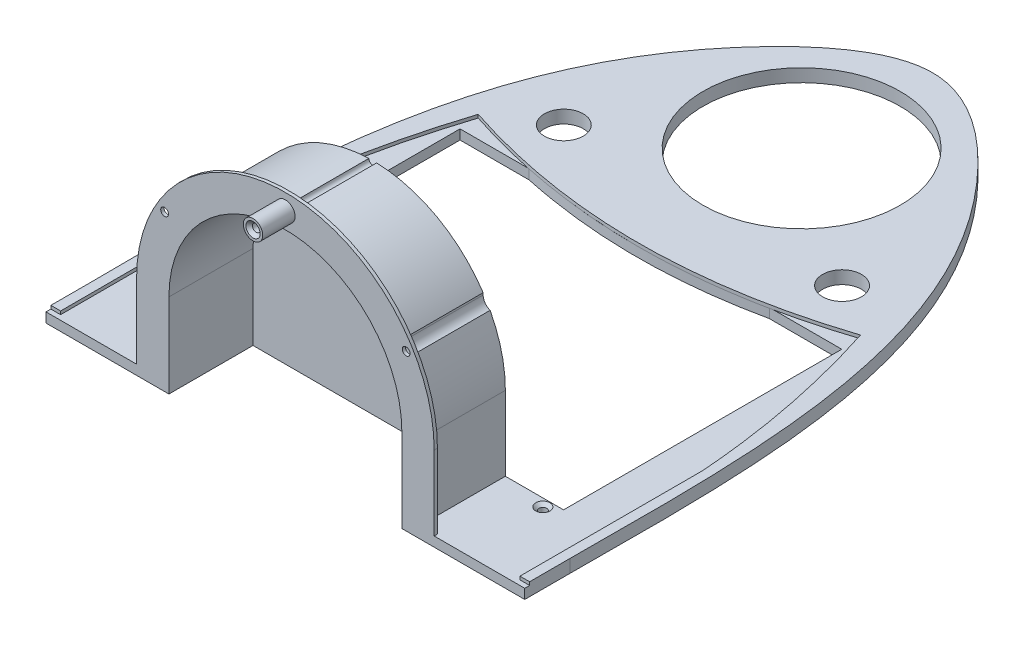
SolidWorks part; units mm, degrees
material "PET"
ref_plane "Front" through (0, 0, 0) normal (0, 0, 1) x (1, 0, 0)
ref_plane "Top" through (0, 0, 0) normal (0, 1, 0) x (1, 0, 0)
ref_plane "Right" through (0, 0, 0) normal (1, 0, 0) x (0, 0, -1)
sketch "Sketch3" plane through (0, 0, 0) normal (0, 1, 0) x (1, 0, 0)
  line L6 (-74, 0) -> (-74, -14)
  line L7 (-74, -14) -> (74, -14)
  line L8 (74, -14) -> (74, 0)
  circle A0 centre (0, 145.589) radius 30.5008
  circle A1 centre (-43.002, 115.0882) radius 5.9957
  circle A2 centre (43.0023, 115.0882) radius 6.0049
  spline S0 degree 3 poles (74, 0) (74.2312, 56.044) (77.0237, 134.8914) (0.0005, 195.647) (-77.0188, 134.8892) (-74.2322, 56.0447) (-74, 0) knots 0 0 0 0 0.40663 0.500002 0.593368 1 1 1 1
extrude "Boss-Extrude1" add sketch "Sketch3" along normal blind 4
sketch "Sketch4" plane through (0, 4, 0) normal (0, 1, 0) x (1, 0, 0)
  line L6 (71.0001, 44.0011) -> (71.0001, 6.0671)
  line L8 (71.0001, 5.9382) -> (71.0001, -16.9987)
  line L9 (-70.9967, 6.0027) -> (-70.9967, 44.0011)
  line L11 (71.0001, -16.9987) -> (-70.9967, -16.9987)
  line L12 (-70.9967, -16.9987) -> (-70.9967, 6.0027)
  line L14 (-38.3482, 99.0875) -> (-43.002, 99.0875)
  line L15 (71.0001, 6.0671) -> (71.0001, 5.9382)
  spline S2 degree 3 poles (-59.0924, 104.7018) (-39.395, 98.236) (0.0027, 91.7694) (39.4006, 98.2356) (59.1009, 104.7026) knots 0.007529 0.007529 0.007529 0.007529 0.499976 0.992492 0.992492 0.992492 0.992492
  spline S3 degree 3 poles (59.1009, 104.7026) (65.5244, 84.7081) (69.4908, 64.4742) (71.0001, 44.0011) knots 0.003068 0.003068 0.003068 0.003068 0.620646 0.620646 0.620646 0.620646
  spline S4 degree 3 poles (-59.0924, 104.7018) (-65.5187, 84.7077) (-69.4868, 64.4742) (-70.9967, 44.0011) knots 0.003077 0.003077 0.003077 0.003077 0.62065 0.62065 0.62065 0.62065
extrude "Cut-Extrude1" cut sketch "Sketch4" against normal blind 1 and the other way through all
sketch "Sketch5" plane through (0, 3, 0) normal (0, 1, 0) x (1, 0, 0)
  line L0 (-37.6312, 99) -> (-59.0046, 99)
  line L1 (36.6037, 99) -> (59.004, 99)
  line L2 (-59.0046, 99) -> (-59.0046, 13)
  line L5 (59.004, 99) -> (59.004, 13)
  line L6 (59.004, 13) -> (-59.0046, 13)
  spline S0 degree 2 poles (-37.6312, 99) (-0.5019, 91.0036) (36.6037, 99) knots 0 0 0 1 1 1
  spline S1 degree 3 poles (59.1009, 104.7026) (19.703, 91.7695) (-19.6948, 91.7692) (-59.0924, 104.7018) knots 0.007529 0.007529 0.007529 0.007529 0.992492 0.992492 0.992492 0.992492 construction
  dimension "D1" = 86
extrude "Cut-Extrude2" cut sketch "Sketch5" against normal blind 10
sketch "Sketch7" plane through (0, 3, 0) normal (0, 1, 0) x (1, 0, 0)
  line L0 (-0.0003, 13) -> (-45.9987, 13)
  line L1 (-59.0046, 13) -> (59.004, 13) construction
  line L2 (-45.9987, 13) -> (-45.9987, -14)
  line L3 (-70.9967, -14) -> (71.0001, -14) construction
  line L4 (-45.9987, -14) -> (0.0017, -14)
  line L5 (0.0017, -14) -> (46.0044, -14)
  line L6 (46.0044, -14) -> (46.0044, 13)
  line L7 (46.0044, 13) -> (-0.0003, 13)
extrude "Boss-Extrude2" add sketch "Sketch7" along normal blind 23
sketch "Sketch8" plane through (0, 26, 0) normal (0, 1, 0) x (1, 0, 0)
  line L0 (0.0029, 13) -> (0.0029, -14)
  line L1 (46.0044, 13) -> (-45.9987, 13) construction
  line L2 (-45.9987, -14) -> (46.0044, -14) construction
  line L3 (0.0029, -14) -> (-45.9987, -14)
  line L4 (-45.9987, -14) -> (-45.9987, 13)
  line L5 (-45.9987, 13) -> (0.0029, 13)
revolve "Revolve1" add sketch "Sketch8" angle 180 about L0
sketch "Sketch9" plane through (0, 0, -13) normal (0, 0, -1) x (-1, 0, 0)
  line L0 (-0.0029, 67.0051) -> (-0.0029, 66.9999)
  line L2 (74.091, 4) -> (-74.0909, 4) construction
  line L3 (-46.0044, 26) -> (-46.0044, 3) construction
  line L5 (45.9987, 26) -> (45.9987, 3) construction
  line L6 (-46.0044, 4) -> (-46.0044, 26)
  line L7 (-41.0083, 4) -> (-41.0083, 26)
  line L8 (41.002, 4) -> (41.002, 26)
  line L9 (45.9987, 3) -> (45.9987, 4)
  line L10 (45.9987, 4) -> (45.9987, 26)
  line L11 (41.002, 4) -> (41.002, 3)
  line L12 (41.002, 3) -> (45.9987, 3)
  line L13 (-46.0044, 3) -> (-46.0044, 4)
  line L14 (-46.0044, 3) -> (-41.0083, 3)
  line L15 (-41.0083, 3) -> (-41.0083, 4)
  arc A1 (-41.0083, 26) -> (41.002, 26) centre (-0.0031, 26) cw
  arc A2 (-46.0044, 26) -> (45.9987, 26) centre (-0.0029, 26) cw
extrude "Cut-Extrude3" cut sketch "Sketch9" against normal blind 26
fillet "Fillet1" radius 1 3 edges at (-41.002, 14.5, 13) (41.0083, 14.5, 13) (0.0031, 67.0051, 13)
sketch "Sketch10" plane through (0, 0, -13) normal (0, 0, -1) x (-1, 0, 0)
  point P8 (-37.3413, 48.1051)
  point P10 (37.3365, 48.1051)
hole_wizard "CSK for M2 Countersunk Raised Head Screw1" positions "3DSketch1" profile "Sketch11" countersink size "M2" standard "ISO" end condition up to next
sketch3d "3DSketch1"
  point P0 (37.3413, 48.1051, -13)
sketch "Sketch11" plane through (37.3413, 48.1051, -13) normal (1, 0, 0) x (0, 1, 0)
  line L0 (0, 0) -> (0, 27)
  line L1 (0, 27) -> (1.2, 27)
  line L2 (1.2, 27) -> (1.2, 1)
  line L3 (1.2, 1) -> (2.2, 0)
  line L5 (2.2, 0) -> (0, 0)
  line L6 (-1.2, 1) -> (-2.2, 0) construction
  line L11 (0, -6.35) -> (0, 107.95) construction
  dimension "Thru Hole Dia." = 2.4
  dimension "Thru Hole Depth" = 27
  dimension "Near C'Sink Dia." = 4.4
  dimension "Near C'Sink Angle" = 90
hole_wizard "CSK for M2 Countersunk Raised Head Screw2" positions "3DSketch2" profile "Sketch12" countersink size "M2" standard "ISO" end condition up to next
sketch3d "3DSketch2"
  point P0 (-37.3365, 48.1051, -13)
sketch "Sketch12" plane through (-37.3365, 48.1051, -13) normal (1, 0, 0) x (0, 1, 0)
  line L0 (0, 0) -> (0, 27)
  line L1 (0, 27) -> (1.2, 27)
  line L2 (1.2, 27) -> (1.2, 1)
  line L3 (1.2, 1) -> (2.2, 0)
  line L5 (2.2, 0) -> (0, 0)
  line L6 (-1.2, 1) -> (-2.2, 0) construction
  line L11 (0, -6.35) -> (0, 107.95) construction
  dimension "Thru Hole Dia." = 2.4
  dimension "Thru Hole Depth" = 27
  dimension "Near C'Sink Dia." = 4.4
  dimension "Near C'Sink Angle" = 90
sketch "Sketch13" plane through (0, 0, 13) normal (0, 0, -1) x (-1, 0, 0)
  line L9 (-40.5371, 48.1051) -> (-40.5371, 50.1197)
  line L10 (-34.1425, 48.1051) -> (-34.1425, 57.9344)
  line L11 (-34.1425, 57.9344) -> (-40.5371, 50.1197)
  line L12 (34.133, 48.1051) -> (34.133, 58.5672)
  line L13 (34.133, 58.5672) -> (40.5348, 50.9806)
  line L14 (40.5348, 50.9806) -> (40.5348, 48.1051)
  arc A3 (-40.5371, 48.1051) -> (-37.3413, 44.9022) centre (-37.3377, 48.1016) ccw
  arc A7 (-37.3413, 44.9022) -> (-34.1425, 48.1051) centre (-37.3433, 48.1031) ccw
  arc A9 (40.5348, 48.1051) -> (37.3365, 44.9022) centre (37.3342, 48.1029) cw
  arc A10 (37.3365, 44.9022) -> (34.133, 48.1051) centre (37.3342, 48.1035) cw
extrude "Cut-Extrude4" cut sketch "Sketch13" along normal blind 26
sketch "Sketch14" plane through (0, 0, 14) normal (0, 0, 1) x (1, 0, 0)
  line L1 (-36.0016, 3) -> (-36.0016, -2.0033)
  line L2 (-36.0016, 26) -> (46.0044, 26)
  line L3 (-36.0016, 3) -> (-36.0016, 26)
  line L4 (36.0041, 3) -> (36.0041, 26)
  line L5 (0.0029, 62.0029) -> (0.0029, 62.0011)
  line L6 (36.0041, 3) -> (36.0041, -2.0033)
  line L7 (36.0041, -2.0033) -> (-36.0016, -2.0033)
  arc A1 (-36.0016, 26) -> (36.0041, 26) centre (0.0013, 26) cw
extrude "Cut-Extrude6" cut sketch "Sketch14" against normal blind 26
sketch "Sketch19" plane through (0, 3, 0) normal (0, 1, 0) x (1, 0, 0)
  point P5 (-54.9995, 10.6037)
  point P7 (54.9997, 10.6037)
hole_wizard "CSK for M2 Countersunk Raised Head Screw3" positions "3DSketch3" profile "Sketch20" countersink size "M2" standard "ISO" end condition up to next
sketch3d "3DSketch3"
  point P0 (-54.9995, 3, -10.6037)
  point P3 (54.9997, 3, -10.6037)
sketch "Sketch20" plane through (-54.9995, 3, -10.6037) normal (1, 0, 0) x (0, 0, 1)
  line L0 (0, 0) -> (0, 3)
  line L1 (0, 3) -> (1.2, 3)
  line L2 (1.2, 3) -> (1.2, 1)
  line L3 (1.2, 1) -> (2.2, 0)
  line L5 (2.2, 0) -> (0, 0)
  line L6 (-1.2, 1) -> (-2.2, 0) construction
  line L11 (0, -6.35) -> (0, 107.95) construction
  dimension "Thru Hole Dia." = 2.4
  dimension "Thru Hole Depth" = 3
  dimension "Near C'Sink Dia." = 4.4
  dimension "Near C'Sink Angle" = 90
sketch "Sketch21" plane through (0, 4, 0) normal (0, 1, 0) x (1, 0, 0)
  line L0 (-70.9967, -14) -> (-70.9967, -12.4958)
  line L5 (-70.9967, -14) -> (-70.9967, 44.0011) construction
  line L6 (-70.9967, -12.4958) -> (-74.2003, -12.4958)
  line L7 (-74.2003, -12.4958) -> (-74.2003, -14)
  line L8 (-74.2003, -14) -> (-70.9967, -14)
  line L10 (71.0001, -14) -> (74.3798, -14)
  line L11 (71.0001, -14) -> (71.0001, -12.4958)
  line L12 (71.0001, -12.4958) -> (74.3798, -12.4958)
  line L13 (74.3798, -14) -> (74.3798, -12.4958)
extrude "Cut-Extrude7" cut sketch "Sketch21" against normal blind 1
ref_plane "Plane1" through (0, 0, 14) normal (0, 0, 1) x (1, 0, 0)
sketch "Sketch26" plane through (0, 0, 14) normal (0, 0, 1) x (1, 0, 0)
  circle A1 centre (0.0029, 67.0015) radius 3.002
  point P3 (0.0029, 67.0015)
extrude "Boss-Extrude4" add sketch "Sketch26" along normal blind 10
hole_wizard "CSK for M2 Countersunk Flat Head Screw1" positions "Sketch27" profile "Sketch28" countersink size "M2" standard "ISO" end condition up to next
sketch "Sketch27" plane through (0, 0, 24) normal (0, 0, 1) x (1, 0, 0)
  point P0 (0.0029, 67.0015)
sketch "Sketch28" plane through (0.0029, 67.0015, 24) normal (1, 0, 0) x (0, -1, 0)
  line L0 (0, 0) -> (0, 37)
  line L1 (0, 37) -> (1.2, 37)
  line L2 (1.2, 37) -> (1.2, 1)
  line L3 (1.2, 1) -> (2.2, 0)
  line L5 (2.2, 0) -> (0, 0)
  line L6 (-1.2, 1) -> (-2.2, 0) construction
  line L11 (0, -6.35) -> (0, 107.95) construction
  dimension "Thru Hole Dia." = 2.4
  dimension "Thru Hole Depth" = 37
  dimension "Near C'Sink Dia." = 4.4
  dimension "Near C'Sink Angle" = 90
